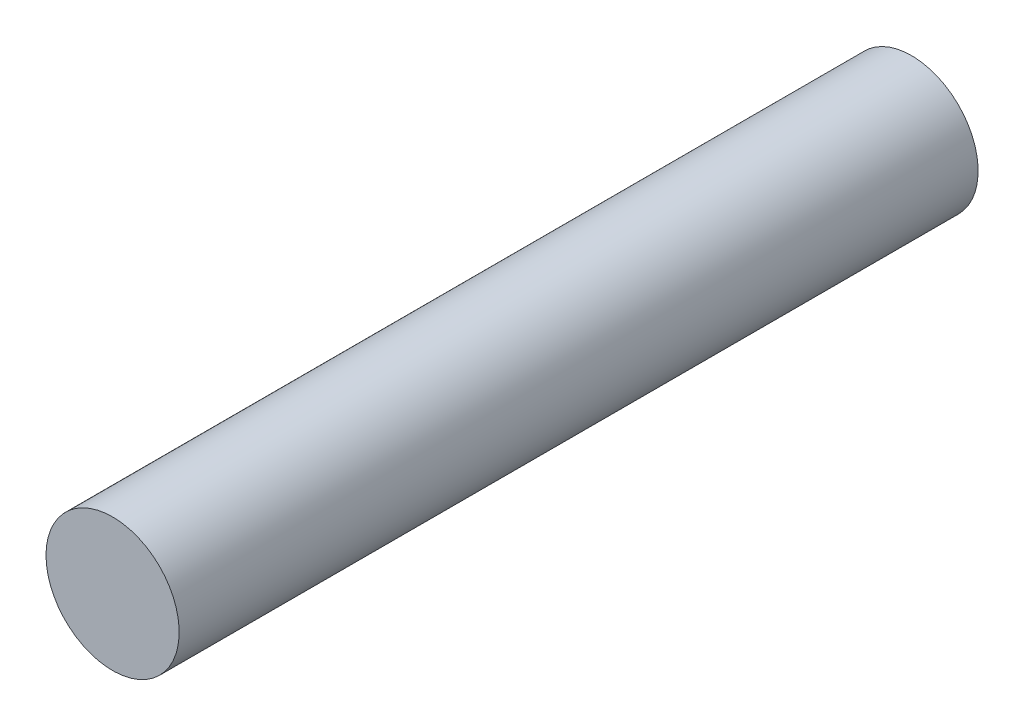
SolidWorks part; units mm, degrees
ref_plane "Front Plane" through (0, 0, 0) normal (0, 0, 1) x (1, 0, 0)
ref_plane "Top Plane" through (0, 0, 0) normal (0, 1, 0) x (1, 0, 0)
ref_plane "Right Plane" through (0, 0, 0) normal (1, 0, 0) x (0, 0, -1)
sketch "Sketch1" plane through (0, 0, 0) normal (0, 0, 1) x (1, 0, 0)
  circle A0 centre (0, 0) radius 12.7
  dimension "D1" = 25.4
extrude "Boss-Extrude1" add sketch "Sketch1" along normal blind 152.4
